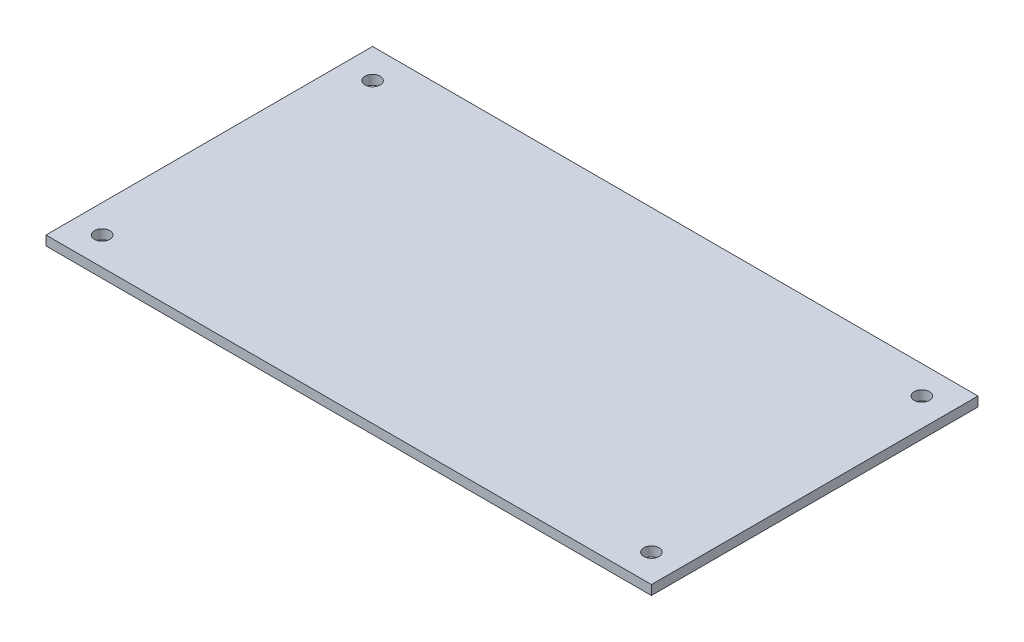
SolidWorks part; units mm, degrees
ref_plane "Front Plane" through (0, 0, 0) normal (0, 0, 1) x (1, 0, 0)
ref_plane "Top Plane" through (0, 0, 0) normal (0, 1, 0) x (1, 0, 0)
ref_plane "Right Plane" through (0, 0, 0) normal (1, 0, 0) x (0, 0, -1)
sketch "Sketch1" plane through (0, 0, 0) normal (0, 1, 0) x (1, 0, 0)
  line L1 (-100.2761, -42.0212) -> (26.7239, -42.0212)
  line L2 (-100.2761, -42.0212) -> (-100.2761, 26.4788)
  line L3 (-100.2761, 26.4788) -> (26.7239, 26.4788)
  line L4 (26.7239, -42.0212) -> (26.7239, 26.4788)
  line L5 (-100.2761, -42.0212) -> (26.7239, 26.4788) construction
  line L6 (-100.2761, 26.4788) -> (26.7239, -42.0212) construction
  dimension "D1" = 127
  dimension "D2" = 68.5
extrude "Boss-Extrude1" add sketch "Sketch1" along normal blind 2
sketch "Sketch2" plane through (0, 2, 0) normal (0, 1, 0) x (1, 0, 0)
  line L0 (-100.2761, 26.4788) -> (-100.2761, -42.0212) construction
  line L1 (26.7239, 26.4788) -> (-100.2761, 26.4788) construction
  line L2 (26.7239, -42.0212) -> (26.7239, 26.4788) construction
  line L3 (-100.2761, -42.0212) -> (26.7239, -42.0212) construction
  circle A0 centre (-94.0761, 20.2788) radius 1.6
  circle A1 centre (-94.3861, -36.1312) radius 1.6
  circle A2 centre (20.8339, -36.1312) radius 1.6
  circle A3 centre (20.8339, 20.5888) radius 1.6
  point P1 (-94.0761, 20.2788)
  point P2 (20.8339, 20.5888)
  point P3 (-94.3861, -36.1312)
  point P12 (20.8339, -36.1312)
  dimension "D1" = 6.2
  dimension "D2" = 6.2
  dimension "D3" = 5.89
  dimension "D4" = 5.89
  dimension "D5" = 5.89
  dimension "D6" = 5.89
  dimension "D7" = 5.89
  dimension "D8" = 5.89
extrude "Cut-Extrude1" cut sketch "Sketch2" against normal blind 2
